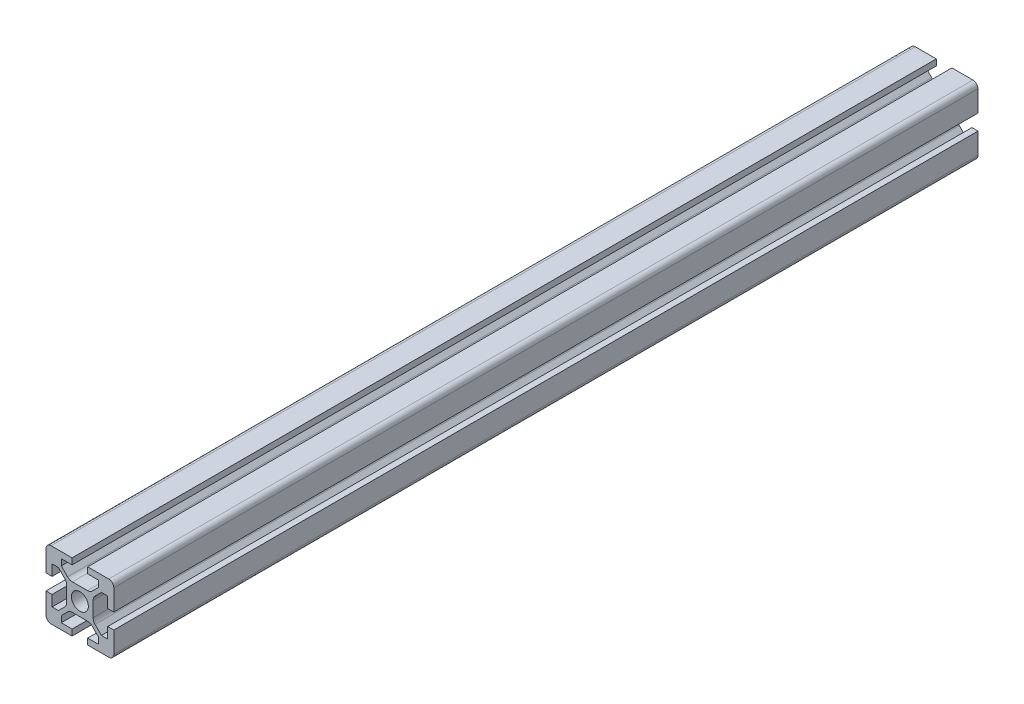
SolidWorks part; units mm, degrees
ref_plane "Alzado" through (0, 0, 0) normal (0, 0, 1) x (1, 0, 0)
ref_plane "Planta" through (0, 0, 0) normal (0, 1, 0) x (1, 0, 0)
ref_plane "Vista lateral" through (0, 0, 0) normal (1, 0, 0) x (0, 0, -1)
sketch "Croquis1" plane through (0, 0, 0) normal (0, 0, 1) x (1, 0, 0)
  line L0 (0, 0) -> (-10, 0) construction
  line L1 (-10, 0) -> (-10, 10) construction
  line L2 (-10, 10) -> (0, 10) construction
  line L3 (0, 10) -> (0, 0) construction
  line L4 (-10, 8.5) -> (-10, 2.3)
  line L5 (-8.2, 2.3) -> (-8.2, 5.5)
  line L6 (-6.3485, 5.5) -> (-4.4858, 3.6373)
  line L7 (-10, 10) -> (0, 0) construction
  line L8 (-3.9, 2.223) -> (-3.9, 0)
  line L9 (-8.2, 5.5) -> (-6.3485, 5.5)
  line L14 (-10, 2.3) -> (-8.2, 2.3)
  line L15 (-2.223, 3.9) -> (0, 3.9)
  line L16 (-5.5, 6.3485) -> (-3.6373, 4.4858)
  line L17 (-5.5, 8.2) -> (-5.5, 6.3485)
  line L18 (-2.3, 10) -> (-2.3, 8.2)
  line L19 (-2.3, 8.2) -> (-5.5, 8.2)
  line L20 (-8.5, 10) -> (-2.3, 10)
  line L21 (8.5, 10) -> (2.3, 10)
  line L22 (2.3, 10) -> (2.3, 8.2)
  line L23 (2.3, 8.2) -> (5.5, 8.2)
  line L24 (5.5, 8.2) -> (5.5, 6.3485)
  line L25 (5.5, 6.3485) -> (3.6373, 4.4858)
  line L26 (2.223, 3.9) -> (0, 3.9)
  line L27 (3.9, 2.223) -> (3.9, 0)
  line L28 (6.3485, 5.5) -> (4.4858, 3.6373)
  line L29 (8.2, 5.5) -> (6.3485, 5.5)
  line L30 (8.2, 2.3) -> (8.2, 5.5)
  line L31 (10, 2.3) -> (8.2, 2.3)
  line L32 (10, 8.5) -> (10, 2.3)
  line L33 (10, -8.5) -> (10, -2.3)
  line L34 (10, -2.3) -> (8.2, -2.3)
  line L35 (8.2, -2.3) -> (8.2, -5.5)
  line L36 (8.2, -5.5) -> (6.3485, -5.5)
  line L37 (6.3485, -5.5) -> (4.4858, -3.6373)
  line L38 (3.9, -2.223) -> (3.9, 0)
  line L39 (2.223, -3.9) -> (0, -3.9)
  line L40 (5.5, -6.3485) -> (3.6373, -4.4858)
  line L41 (5.5, -8.2) -> (5.5, -6.3485)
  line L42 (2.3, -8.2) -> (5.5, -8.2)
  line L43 (2.3, -10) -> (2.3, -8.2)
  line L44 (8.5, -10) -> (2.3, -10)
  line L45 (-8.5, -10) -> (-2.3, -10)
  line L46 (-2.3, -10) -> (-2.3, -8.2)
  line L47 (-2.3, -8.2) -> (-5.5, -8.2)
  line L48 (-5.5, -8.2) -> (-5.5, -6.3485)
  line L49 (-5.5, -6.3485) -> (-3.6373, -4.4858)
  line L50 (-2.223, -3.9) -> (0, -3.9)
  line L51 (-3.9, -2.223) -> (-3.9, 0)
  line L52 (-6.3485, -5.5) -> (-4.4858, -3.6373)
  line L53 (-8.2, -5.5) -> (-6.3485, -5.5)
  line L54 (-8.2, -2.3) -> (-8.2, -5.5)
  line L55 (-10, -2.3) -> (-8.2, -2.3)
  line L56 (-10, -8.5) -> (-10, -2.3)
  arc A0 (-8.5, 10) -> (-10, 8.5) centre (-8.5, 8.5) ccw
  arc A1 (0, 2.5) -> (-2.5, 0) centre (0, 0) ccw
  arc A2 (-3.9, 2.223) -> (-4.4858, 3.6373) centre (-5.9, 2.223) ccw
  arc A3 (-2.223, 3.9) -> (-3.6373, 4.4858) centre (-2.223, 5.9) cw
  arc A4 (2.223, 3.9) -> (3.6373, 4.4858) centre (2.223, 5.9) ccw
  arc A5 (2.5, 0) -> (0, 2.5) centre (0, 0) ccw
  arc A6 (3.9, 2.223) -> (4.4858, 3.6373) centre (5.9, 2.223) cw
  arc A7 (10, 8.5) -> (8.5, 10) centre (8.5, 8.5) ccw
  arc A8 (3.9, -2.223) -> (4.4858, -3.6373) centre (5.9, -2.223) ccw
  arc A9 (0, -2.5) -> (2.5, 0) centre (0, 0) ccw
  arc A10 (2.223, -3.9) -> (3.6373, -4.4858) centre (2.223, -5.9) cw
  arc A11 (8.5, -10) -> (10, -8.5) centre (8.5, -8.5) ccw
  arc A12 (-2.223, -3.9) -> (-3.6373, -4.4858) centre (-2.223, -5.9) ccw
  arc A13 (-2.5, 0) -> (0, -2.5) centre (0, 0) ccw
  arc A14 (-3.9, -2.223) -> (-4.4858, -3.6373) centre (-5.9, -2.223) cw
  arc A15 (-10, -8.5) -> (-8.5, -10) centre (-8.5, -8.5) ccw
  point P92 (0, 0)
  dimension "D3" = 3
  dimension "D9" = 2.5
  dimension "D10" = 2
  dimension "D2" = 10
  dimension "D4" = 6.2
  dimension "D5" = 1.8
  dimension "D6" = 0.6
  dimension "D7" = 6.1
  dimension "D8" = 5.5
  dimension "D11" = 4
extrude "Saliente-Extruir1" add sketch "Croquis1" along normal blind 255
